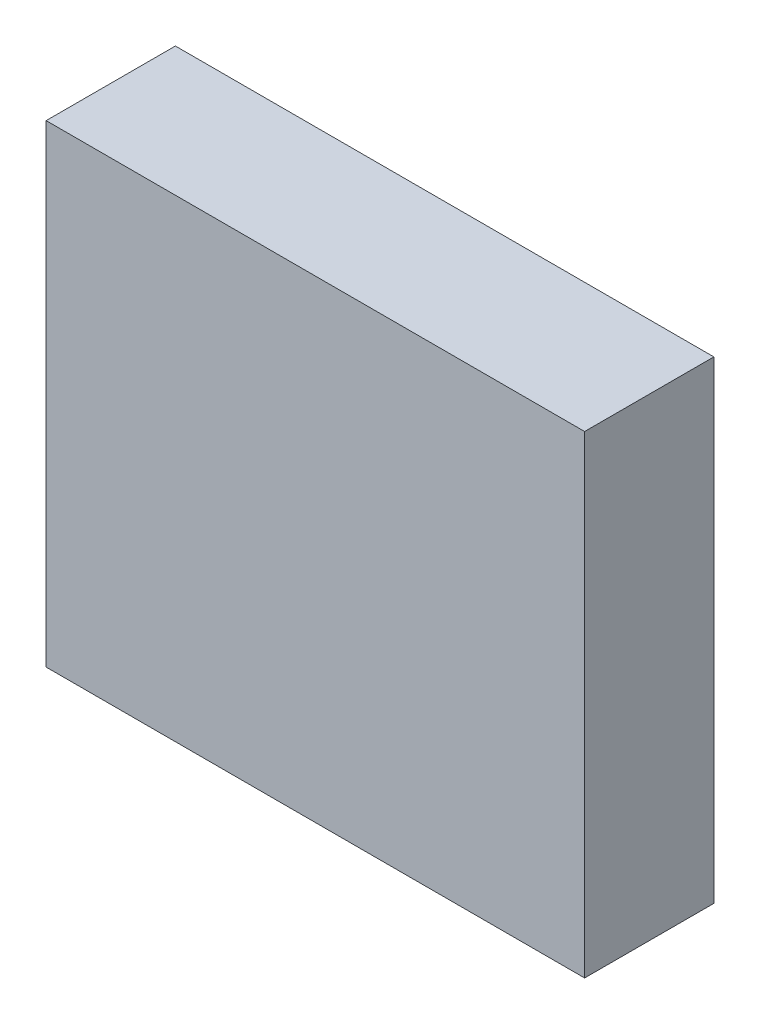
SolidWorks part; units mm, degrees
ref_plane "Front Plane" through (0, 0, 0) normal (0, 0, 1) x (1, 0, 0)
ref_plane "Top Plane" through (0, 0, 0) normal (0, 1, 0) x (1, 0, 0)
ref_plane "Right Plane" through (0, 0, 0) normal (1, 0, 0) x (0, 0, -1)
sketch "Sketch1" plane through (0, 0, 0) normal (0, 0, 1) x (1, 0, 0)
  line L0 (-2.2666, 1.9872) -> (1.9, 1.9872)
  line L1 (1.9, 1.9872) -> (1.9, -1.675)
  line L2 (1.9, -1.675) -> (-2.2666, -1.675)
  line L3 (-2.2666, -1.675) -> (-2.2666, 1.9872)
extrude "Component_Outline" add sketch "Sketch1" along normal blind 1 separate body
sketch3d "3DSketch1"
  line L0 (0, 0, 0) -> (1, 0, 0)
  line L1 (0, 0, 0) -> (0, 1, 0)
  line L2 (0, 0, 0) -> (0, 0, 1)
  point P0 (0, 0, 0)
